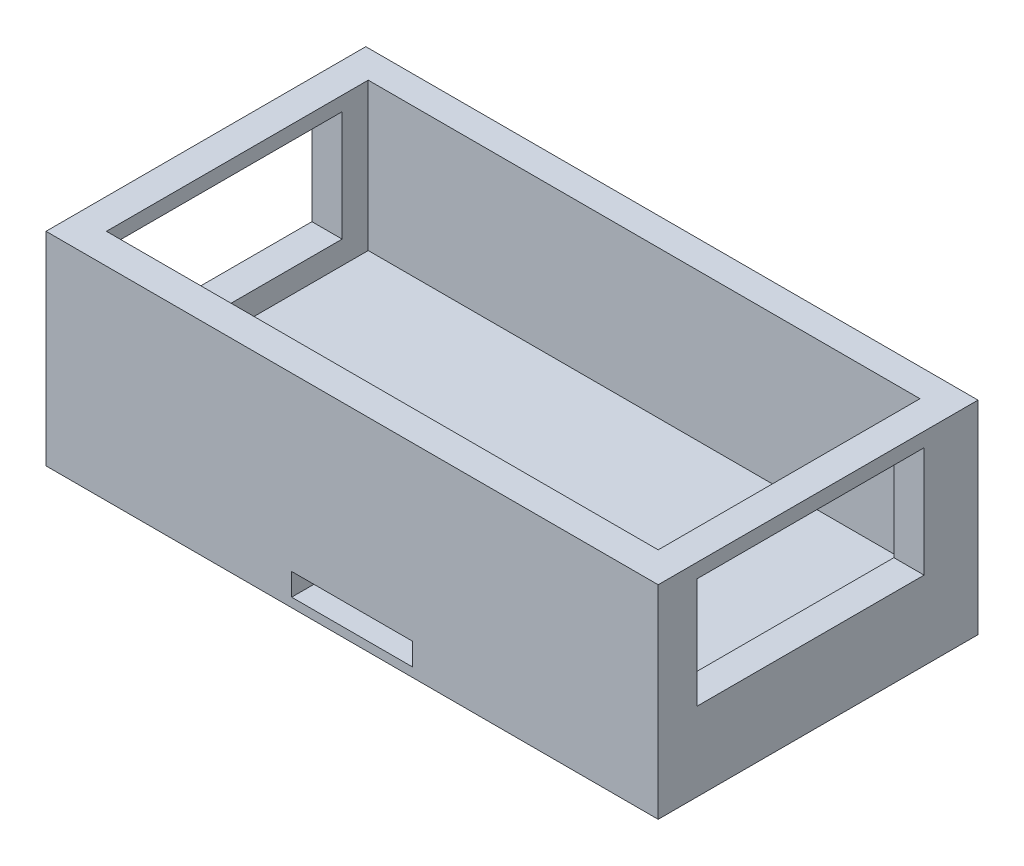
SolidWorks part; units mm, degrees
ref_plane "Front Plane" through (0, 0, 0) normal (0, 0, 1) x (1, 0, 0)
ref_plane "Top Plane" through (0, 0, 0) normal (0, 1, 0) x (1, 0, 0)
ref_plane "Right Plane" through (0, 0, 0) normal (1, 0, 0) x (0, 0, -1)
sketch "Sketch1" plane through (0, 0, 0) normal (0, 1, 0) x (1, 0, 0)
  line L1 (0, 0) -> (128.651, 0)
  line L2 (0, 0) -> (0, 67.2084)
  line L3 (0, 67.2084) -> (128.651, 67.2084)
  line L4 (128.651, 0) -> (128.651, 67.2084)
  point P5 (128.0485, 64.4624)
  point P6 (115.974, 44.0136)
extrude "Boss-Extrude1" add sketch "Sketch1" along normal blind 42.6974
sketch "Sketch2" plane through (0, 42.6974, 0) normal (0, 1, 0) x (1, 0, 0)
  line L1 (6.35, 6.35) -> (122.301, 6.35)
  line L2 (6.35, 6.35) -> (6.35, 61.3664)
  line L3 (6.35, 61.3664) -> (122.301, 61.3664)
  line L4 (122.301, 6.35) -> (122.301, 61.3664)
  point P4 (122.2647, 61.2859)
  point P5 (121.5673, 58.9121)
extrude "Cut-Extrude1" cut sketch "Sketch2" against normal blind 31.0134
sketch "Sketch3" plane through (0, 0, 0) normal (0, 0, 1) x (1, 0, 0)
  line L1 (51.6255, 1.9194) -> (77.0255, 1.9194)
  line L2 (51.6255, 1.9194) -> (51.6255, 6.604)
  line L3 (51.6255, 6.604) -> (77.0255, 6.604)
  line L4 (77.0255, 1.9194) -> (77.0255, 6.604)
  point P4 (68.859, 5.0081)
extrude "Cut-Extrude2" cut sketch "Sketch3" against normal blind 67.7164
sketch "Sketch5" plane through (128.651, 0, 0) normal (1, 0, 0) x (0, 0, -1)
  line L1 (8.128, 16.51) -> (55.88, 16.51)
  line L2 (8.128, 16.51) -> (8.128, 39.6953)
  line L3 (8.128, 39.6953) -> (55.88, 39.6953)
  line L4 (55.88, 16.51) -> (55.88, 39.6953)
  point P4 (7.8127, 16.6641)
  point P5 (59.656, 16.7161)
extrude "Cut-Extrude3" cut sketch "Sketch5" against normal blind 6.35
ref_plane "Plane1" through (64.3255, 0, 0) normal (-1, 0, 0) x (0, 0, 1)
mirror "Mirror1" about plane through (64.3255, 0, 0) normal (-1, 0, 0) of "Cut-Extrude3"
